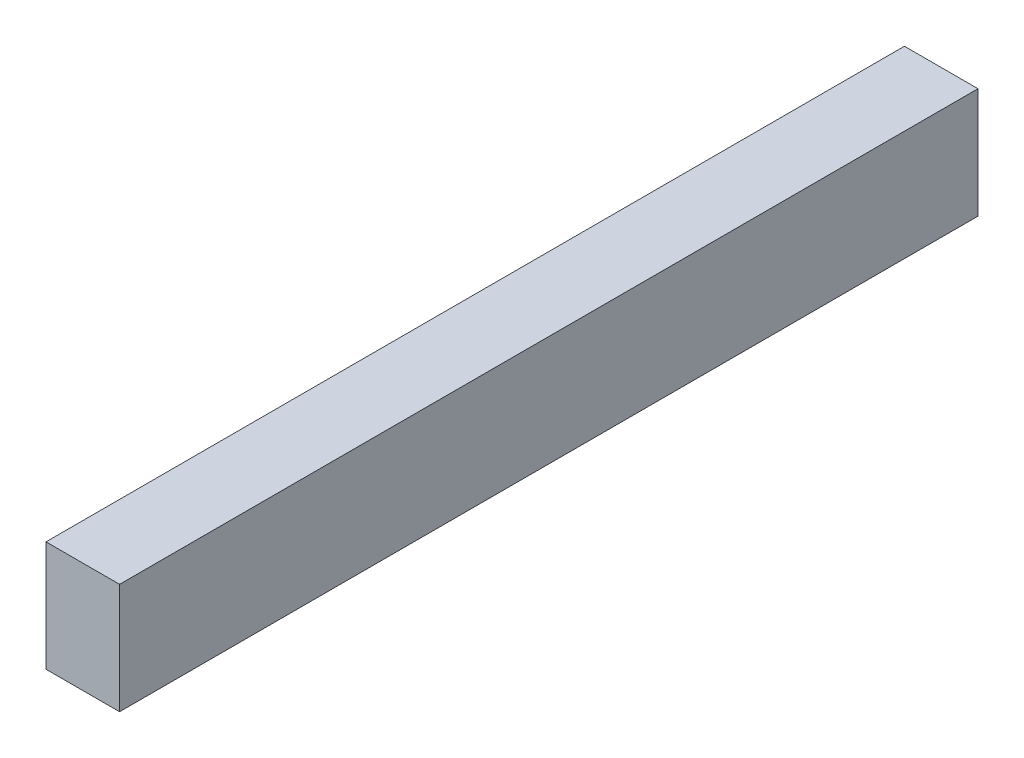
SolidWorks part; units mm, degrees
ref_plane "Front Plane" through (0, 0, 0) normal (0, 0, 1) x (1, 0, 0)
ref_plane "Top Plane" through (0, 0, 0) normal (0, 1, 0) x (1, 0, 0)
ref_plane "Right Plane" through (0, 0, 0) normal (1, 0, 0) x (0, 0, -1)
sketch "Sketch2" plane through (0, 0, 0) normal (0, 1, 0) x (1, 0, 0)
  line L1 (-22.3448, 24.9606) -> (-4.3448, 24.9606)
  line L2 (-22.3448, 24.9606) -> (-22.3448, -185.0394)
  line L3 (-22.3448, -185.0394) -> (-4.3448, -185.0394)
  line L4 (-4.3448, 24.9606) -> (-4.3448, -185.0394)
  line L5 (-22.3448, 24.9606) -> (-4.3448, -185.0394) construction
  line L6 (-22.3448, -185.0394) -> (-4.3448, 24.9606) construction
  point P4 (-13.3448, -80.0394)
  dimension "D1" = 18
  dimension "D2" = 210
extrude "Boss-Extrude1" add sketch "Sketch2" along normal blind 27
